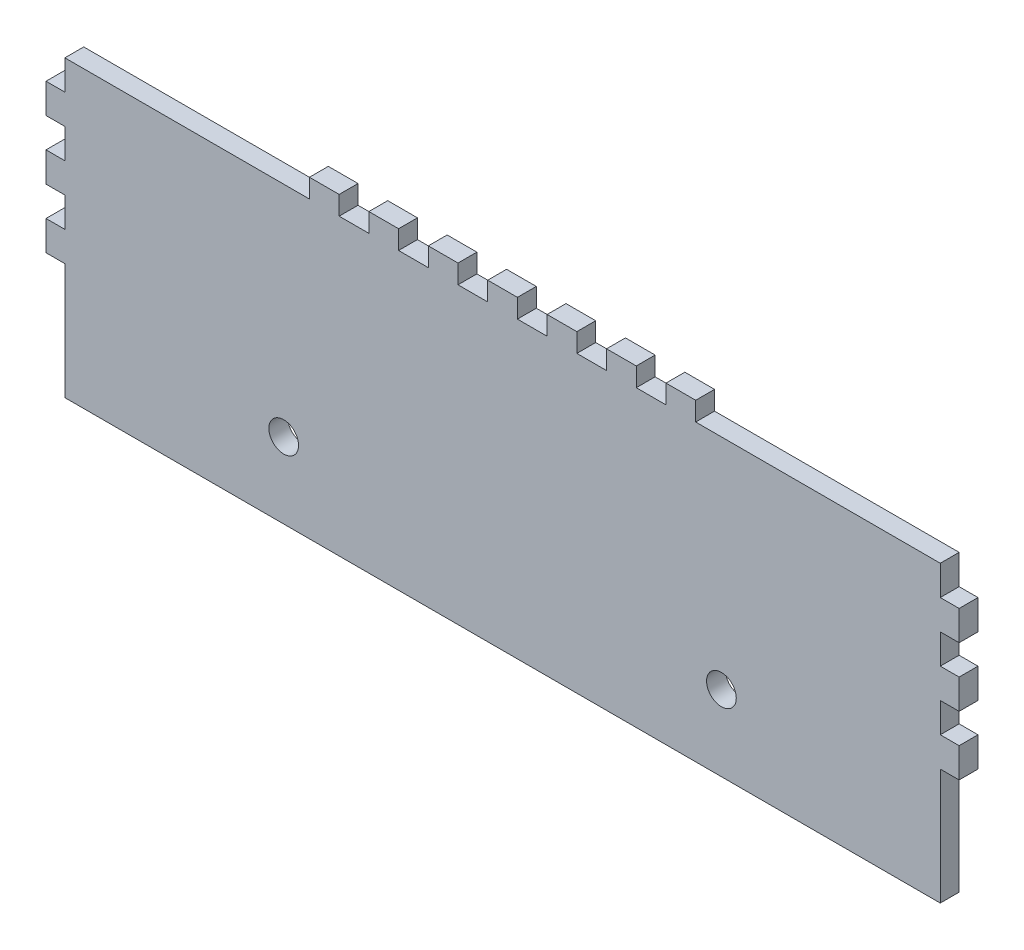
SolidWorks part; units mm, degrees
ref_plane "Front Plane" through (0, 0, 0) normal (0, 0, 1) x (1, 0, 0)
ref_plane "Top Plane" through (0, 0, 0) normal (0, 1, 0) x (1, 0, 0)
ref_plane "Right Plane" through (0, 0, 0) normal (1, 0, 0) x (0, 0, -1)
sketch "Sketch1" plane through (0, 0, 0) normal (0, 0, 1) x (1, 0, 0)
  line L0 (-147.32, -36.83) -> (0, -36.83) construction
  line L1 (-147.32, 0) -> (-106.16, 0)
  line L2 (0, 0) -> (0, -5)
  line L3 (0, -49.53) -> (-147.32, -49.53)
  line L4 (-147.32, 0) -> (-147.32, -5)
  line L7 (-51.16, 0) -> (-46.16, 0)
  line L8 (-46.16, 0) -> (-46.16, 3.175)
  line L9 (-46.16, 3.175) -> (-41.16, 3.175)
  line L16 (-106.16, 0) -> (-106.16, 3.175)
  line L17 (-106.16, 3.175) -> (-101.16, 3.175)
  line L18 (-101.16, 0) -> (-101.16, 3.175)
  line L19 (-101.16, 0) -> (-96.16, 0)
  line L20 (-96.16, 0) -> (-96.16, 3.175)
  line L21 (-96.16, 3.175) -> (-91.16, 3.175)
  line L22 (-91.16, 0) -> (-91.16, 3.175)
  line L23 (-91.16, 0) -> (-86.16, 0)
  line L24 (-86.16, 0) -> (-86.16, 3.175)
  line L25 (-86.16, 3.175) -> (-81.16, 3.175)
  line L26 (-81.16, 0) -> (-81.16, 3.175)
  line L27 (-81.16, 0) -> (-76.16, 0)
  line L28 (-76.16, 0) -> (-76.16, 3.175)
  line L29 (-76.16, 3.175) -> (-71.16, 3.175)
  line L30 (-71.16, 0) -> (-71.16, 3.175)
  line L31 (-71.16, 0) -> (-66.16, 0)
  line L32 (-66.16, 0) -> (-66.16, 3.175)
  line L33 (-66.16, 3.175) -> (-61.16, 3.175)
  line L34 (-61.16, 0) -> (-61.16, 3.175)
  line L35 (-61.16, 0) -> (-56.16, 0)
  line L36 (-56.16, 0) -> (-56.16, 3.175)
  line L37 (-56.16, 3.175) -> (-51.16, 3.175)
  line L38 (-51.16, 0) -> (-51.16, 3.175)
  line L39 (-41.16, 3.175) -> (-41.16, 0)
  line L40 (-41.16, 0) -> (0, 0)
  line L44 (-147.32, -10) -> (-147.32, -15)
  line L45 (-147.32, -5) -> (-150.495, -5)
  line L47 (-147.32, -15) -> (-150.495, -15)
  line L48 (-147.32, -10) -> (-150.495, -10)
  line L49 (-150.495, -5) -> (-150.495, -10)
  line L50 (-150.495, -15) -> (-150.495, -20)
  line L51 (-147.32, -20) -> (-150.495, -20)
  line L52 (-147.32, -20) -> (-147.32, -25)
  line L53 (-147.32, -25) -> (-150.495, -25)
  line L54 (-150.495, -25) -> (-150.495, -30)
  line L55 (-147.32, -30) -> (-150.495, -30)
  line L56 (-147.32, -30) -> (-147.32, -49.53)
  line L59 (-73.66, 16.022) -> (-73.66, -115.082) construction
  line L60 (3.175, -25) -> (3.175, -30)
  line L61 (3.175, -15) -> (3.175, -20)
  line L62 (3.175, -5) -> (3.175, -10)
  line L63 (3.175, -5) -> (0, -5)
  line L64 (3.175, -10) -> (0, -10)
  line L65 (3.175, -15) -> (0, -15)
  line L66 (3.175, -20) -> (0, -20)
  line L67 (3.175, -25) -> (0, -25)
  line L68 (3.175, -30) -> (0, -30)
  line L69 (0, -20) -> (0, -25)
  line L70 (0, -30) -> (0, -49.53)
  line L71 (0, -10) -> (0, -15)
  circle A0 centre (-110.49, -36.83) radius 2.5
  circle A1 centre (-36.83, -36.83) radius 2.5
  point P72 (-73.66, -49.53)
  dimension "D3" = 36.83
  dimension "D5" = 12.7
  dimension "D6" = 3.175
  dimension "D1" = 5
  dimension "D2" = 73.66
  dimension "D4" = 36.83
  dimension "D9" = 5
  dimension "D10" = 5
  dimension "D12" = 36.83
  dimension "D8" = 3.175
  dimension "D17" = 5
  dimension "D18" = 5
  dimension "D11" = 3
extrude "Boss-Extrude1" add sketch "Sketch1" along normal blind 3.175
sketch "Sketch2" plane through (0, 0, 3.175) normal (0, 0, 1) x (1, 0, 0)
